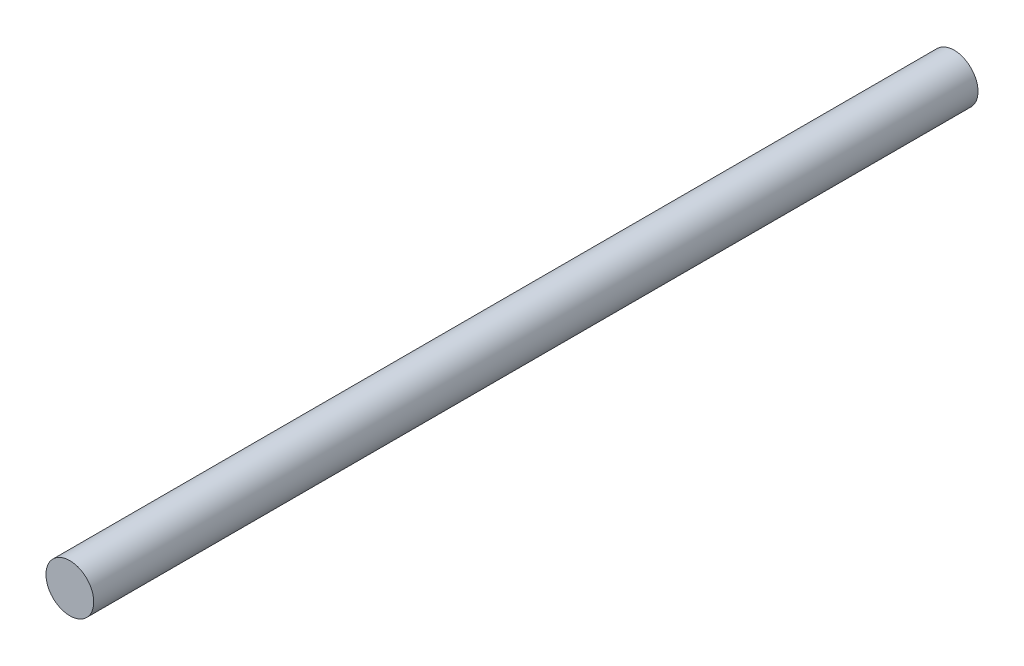
SolidWorks part; units mm, degrees
material "Aluminiumoxid"
ref_plane "Ebene vorne" through (0, 0, 0) normal (0, 0, 1) x (1, 0, 0)
ref_plane "Ebene oben" through (0, 0, 0) normal (0, 1, 0) x (1, 0, 0)
ref_plane "Ebene rechts" through (0, 0, 0) normal (1, 0, 0) x (0, 0, -1)
sketch "Skizze2" plane through (0, 0, 0) normal (0, 0, 1) x (1, 0, 0)
  circle A0 centre (0, 0) radius 10
  dimension "D1" = 20
extrude "Aufsatz-Linear austragen1" add sketch "Skizze2" against normal blind 370
